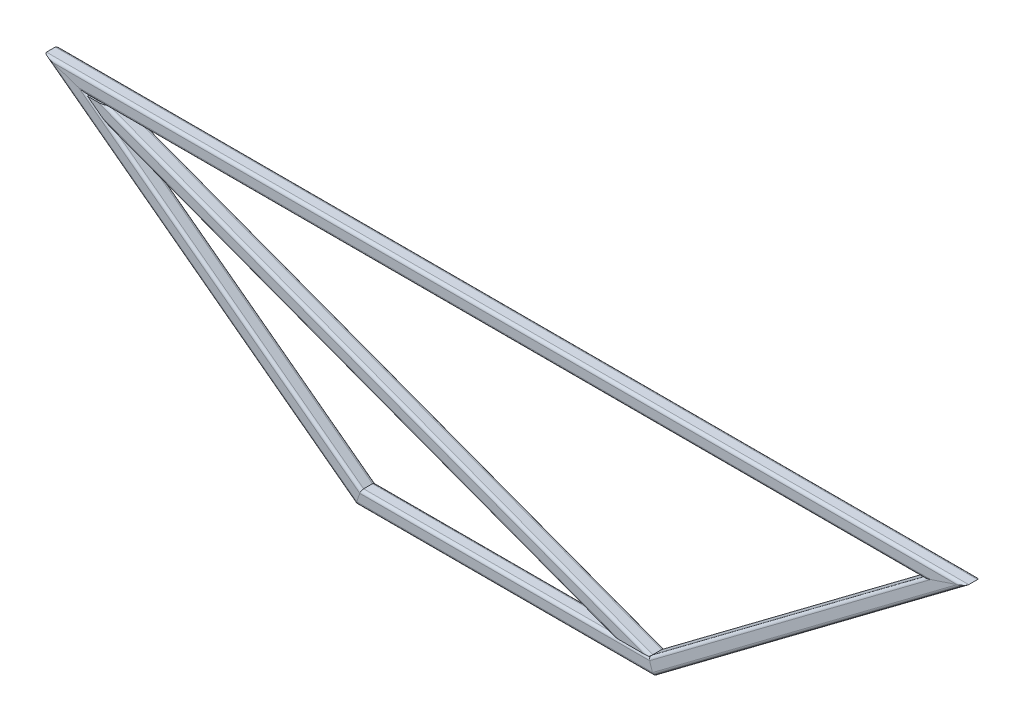
SolidWorks part; units mm, degrees
ref_plane "Front Plane" through (0, 0, 0) normal (0, 0, 1) x (1, 0, 0)
ref_plane "Top Plane" through (0, 0, 0) normal (0, 1, 0) x (1, 0, 0)
ref_plane "Right Plane" through (0, 0, 0) normal (1, 0, 0) x (0, 0, -1)
sketch "Sketch3" plane through (0, 0, 0) normal (0, 0, 1) x (1, 0, 0)
  line L0 (600, 0) -> (-600, 0)
  line L1 (-600, 0) -> (-200, -300)
  line L2 (-200, -300) -> (200, -300)
  line L3 (200, -300) -> (600, 0)
  line L4 (-600, 0) -> (200, -300)
  point P4 (0, 0)
  dimension "D1" = 1200
  dimension "D2" = 400
  dimension "D3" = 500
other "Square tube 20 X 20 X 2(2)"
ref_plane "Plane1" through (600, 0, 0) normal (-1, 0, 0) x (0, -1, 0)
sketch "Sketch15" plane through (600, 0, 0) normal (-1, 0, 0) x (0, -1, 0)
  line L0 (-6, -8) -> (6, -8)
  line L1 (-8, -6) -> (-8, 6)
  line L2 (6, 8) -> (-6, 8)
  line L3 (8, 6) -> (8, -6)
  line L4 (-6, -10) -> (6, -10)
  line L5 (-10, -6) -> (-10, 6)
  line L6 (6, 10) -> (-6, 10)
  line L7 (10, 6) -> (10, -6)
  arc A0 (10, 6) -> (6, 10) centre (6, 6) ccw
  arc A1 (6, -10) -> (10, -6) centre (6, -6) ccw
  arc A2 (-10, -6) -> (-6, -10) centre (-6, -6) ccw
  arc A3 (-6, 10) -> (-10, 6) centre (-6, 6) ccw
  arc A4 (-6, 8) -> (-8, 6) centre (-6, 6) ccw
  arc A5 (8, 6) -> (6, 8) centre (6, 6) ccw
  arc A6 (6, -8) -> (8, -6) centre (6, -6) ccw
  arc A7 (-8, -6) -> (-6, -8) centre (-6, -6) ccw
  point P0 (-10, 0)
  point P1 (10, 0)
  point P2 (0, 10)
  point P3 (0, -10)
  point P4 (0, 0)
  point P5 (-10, -10)
  point P6 (10, -10)
  point P7 (10, 10)
  point P8 (-10, 10)
  point P33 (0, 0)
  dimension "D1" = 4
  dimension "Thickness" = 2
  dimension "V_leg" = 20
other "Square tube 20 X 20 X 2(1)"
ref_plane "Plane2" through (-600, 0, 0) normal (0.9363, -0.3511, 0) x (0.3511, 0.9363, 0)
sketch "Sketch16" plane through (-600, 0, 0) normal (0.9363, -0.3511, 0) x (0.3511, 0.9363, 0)
  line L0 (-6, -8) -> (6, -8)
  line L1 (-8, -6) -> (-8, 6)
  line L2 (6, 8) -> (-6, 8)
  line L3 (8, 6) -> (8, -6)
  line L4 (-6, -10) -> (6, -10)
  line L5 (-10, -6) -> (-10, 6)
  line L6 (6, 10) -> (-6, 10)
  line L7 (10, 6) -> (10, -6)
  arc A0 (10, 6) -> (6, 10) centre (6, 6) ccw
  arc A1 (6, -10) -> (10, -6) centre (6, -6) ccw
  arc A2 (-10, -6) -> (-6, -10) centre (-6, -6) ccw
  arc A3 (-6, 10) -> (-10, 6) centre (-6, 6) ccw
  arc A4 (-6, 8) -> (-8, 6) centre (-6, 6) ccw
  arc A5 (8, 6) -> (6, 8) centre (6, 6) ccw
  arc A6 (6, -8) -> (8, -6) centre (6, -6) ccw
  arc A7 (-8, -6) -> (-6, -8) centre (-6, -6) ccw
  point P0 (-10, 0)
  point P1 (10, 0)
  point P2 (0, 10)
  point P3 (0, -10)
  point P4 (0, 0)
  point P5 (-10, -10)
  point P6 (10, -10)
  point P7 (10, 10)
  point P8 (-10, 10)
  point P33 (0, 0)
  dimension "D1" = 4
  dimension "Thickness" = 2
  dimension "V_leg" = 20
other "Trim/Extend1"
